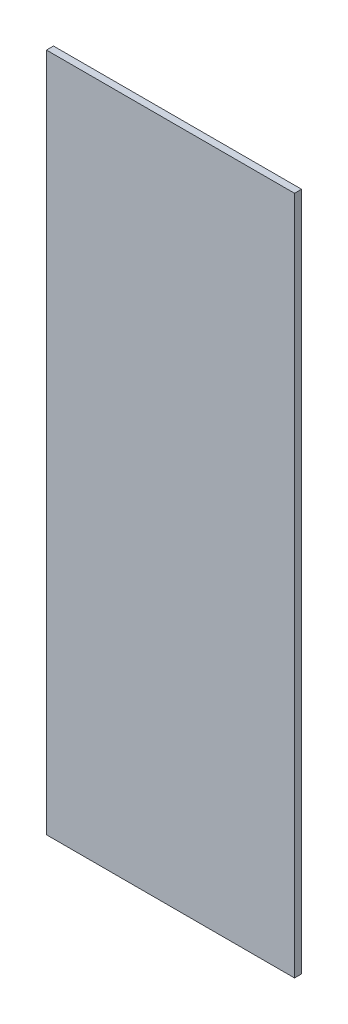
SolidWorks part; units mm, degrees
ref_plane "Front" through (0, 0, 0) normal (0, 0, 1) x (1, 0, 0)
ref_plane "Top" through (0, 0, 0) normal (0, 1, 0) x (1, 0, 0)
ref_plane "Right" through (0, 0, 0) normal (1, 0, 0) x (0, 0, -1)
sketch "Sketch1" plane through (0, 613.7239, 0) normal (0, 0, 1) x (1, 0, 0)
  line L1 (-209.7992, -26.5037) -> (687.6789, -26.5037)
  line L2 (-209.7992, -26.5037) -> (-209.7992, 2432.3426)
  line L3 (-209.7992, 2432.3426) -> (687.6789, 2432.3426)
  line L4 (687.6789, -26.5037) -> (687.6789, 2432.3426)
  point P4 (14434.0592, 2848.6689)
  point P5 (5124.8452, 2828.7774)
  point P6 (0, 0)
  point P7 (757.5626, 2435.5282)
  point P8 (0, 0)
  point P9 (0, 0)
  point P10 (0, 0)
  point P11 (687.6789, 2432.3426)
extrude "Boss-Extrude1" add sketch "Sketch1" along normal blind 25.4
